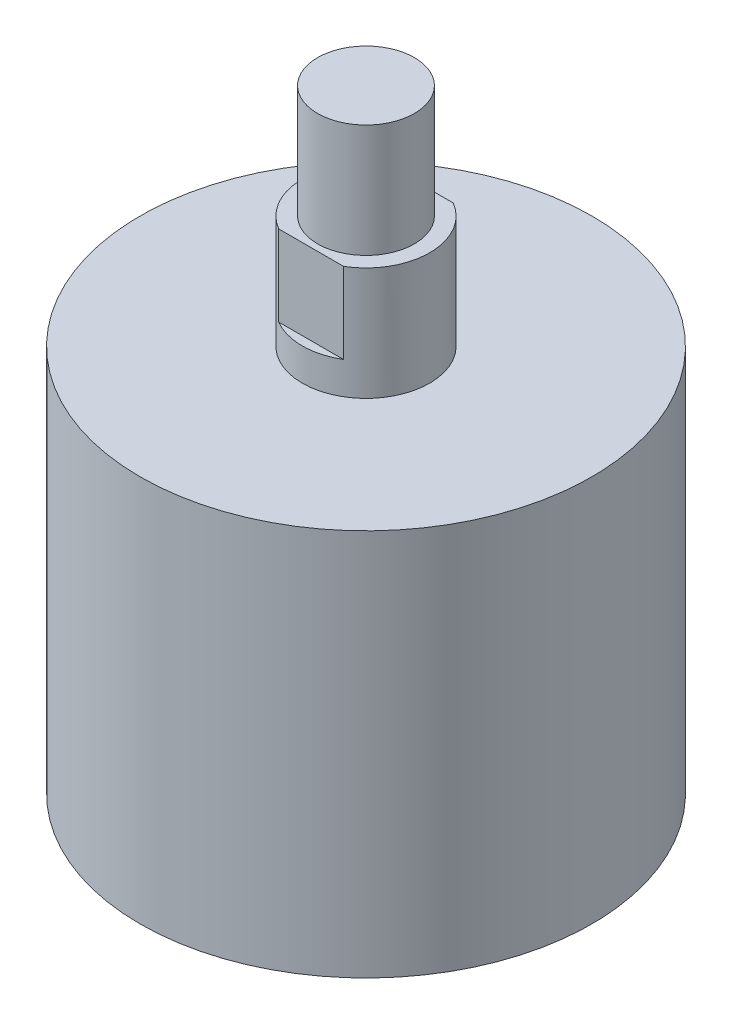
SolidWorks part; units mm, degrees
ref_plane "前视基准面" through (0, 0, 0) normal (0, 0, 1) x (1, 0, 0)
ref_plane "上视基准面" through (0, 0, 0) normal (0, 1, 0) x (1, 0, 0)
ref_plane "右视基准面" through (0, 0, 0) normal (1, 0, 0) x (0, 0, -1)
sketch "Sketch2" plane through (0, 0, 0) normal (0, 1, 0) x (1, 0, 0)
  circle A0 centre (0, 0) radius 14
  dimension "D1" = 28
extrude "Boss-Extrude1" add sketch "Sketch2" along normal blind 24
sketch "Sketch3" plane through (0, 24, 0) normal (0, 1, 0) x (1, 0, 0)
  circle A0 centre (0, 0) radius 3.95
  dimension "D1" = 7.9
extrude "Boss-Extrude2" add sketch "Sketch3" along normal blind 7
sketch "Sketch4" plane through (0, 31, 0) normal (0, 1, 0) x (1, 0, 0)
  circle A0 centre (0, 0) radius 3
  dimension "D1" = 6
extrude "Boss-Extrude3" add sketch "Sketch4" along normal blind 7
sketch "Sketch6" plane through (0, 0, 0) normal (0, -1, 0) x (1, 0, 0)
  line L0 (0, 0) -> (8, 0) construction
  circle A0 centre (8, 0) radius 1.25
  circle A1 centre (0, -8) radius 1.25
  circle A2 centre (-8, 0) radius 1.25
  circle A3 centre (0, 8) radius 1.25
  point P13 (0, 0)
  dimension "D1" = 8
  dimension "D2" = 2.5
  dimension "D3" = 4
extrude "Cut-Extrude1" cut sketch "Sketch6" against normal blind 5
sketch "草图1" plane through (0, 0, 0) normal (0, -1, 0) x (1, 0, 0)
  circle A0 centre (0, 0) radius 3
  dimension "D1" = 6
extrude "凸台-拉伸1" add sketch "草图1" along normal blind 3
sketch "Sketch7" plane through (0, 31, 0) normal (0, 1, 0) x (1, 0, 0)
  line L0 (-2.0106, 3.4) -> (2.0106, 3.4)
  line L1 (-2.0106, -3.4) -> (2.0106, -3.4)
  line L2 (0, 0) -> (3.95, 0) construction
  circle A0 centre (0, 0) radius 3.95 construction
  circle A1 centre (0, 0) radius 3.95
  circle A4 centre (0, 0) radius 3.95 construction
  arc A5 (2.0106, 3.4) -> (-2.0106, 3.4) centre (0, 0) ccw
  arc A6 (-2.0106, -3.4) -> (2.0106, -3.4) centre (0, 0) ccw
  point P2 (-2.0106, 3.4)
  point P4 (3.95, 0)
  point P13 (-1.9183, -3.4529)
  point P14 (2.0106, 3.4)
  point P16 (2.14, -3.3201)
  point P17 (0, -0.0512)
  dimension "D2" = 6.8
  dimension "D1" = 0
extrude "Cut-Extrude2" cut sketch "Sketch7" against normal offset from surface (5 mm away) 2 up to face at (0, 24, 3.95)
